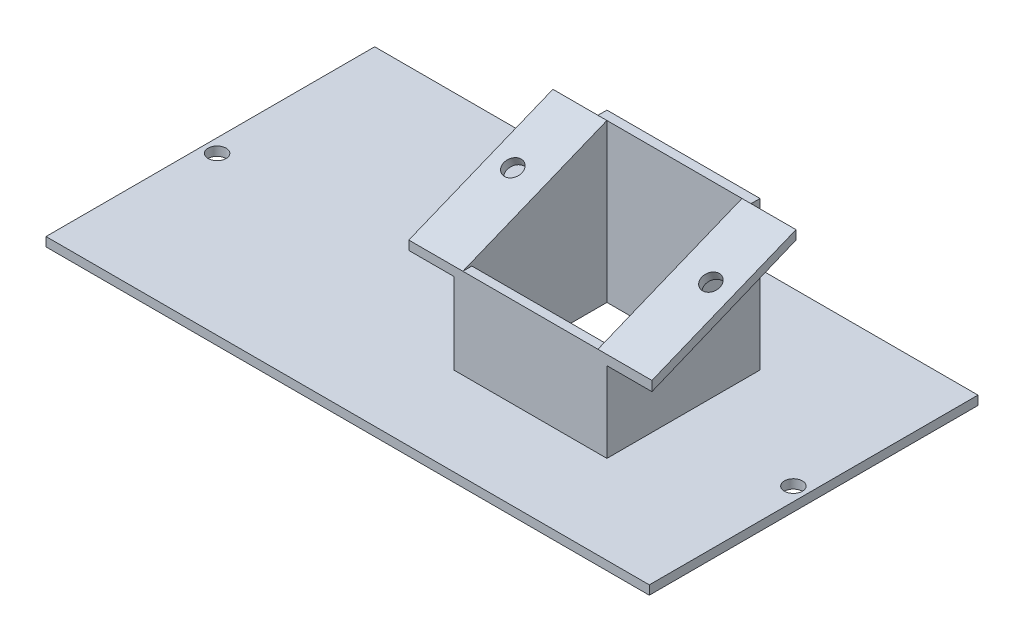
SolidWorks part; units mm, degrees
ref_plane "前视基准面" through (0, 0, 0) normal (0, 0, 1) x (1, 0, 0)
ref_plane "上视基准面" through (0, 0, 0) normal (0, 1, 0) x (1, 0, 0)
ref_plane "右视基准面" through (0, 0, 0) normal (1, 0, 0) x (0, 0, -1)
other "Configuration Table"
sketch "草图1" plane through (0, 0, 0) normal (0, 1, 0) x (1, 0, 0)
  line L1 (-76.1711, 41.9495) -> (57.8289, 41.9495)
  line L2 (-76.1711, 41.9495) -> (-76.1711, -31.0505)
  line L3 (-76.1711, -31.0505) -> (57.8289, -31.0505)
  line L4 (57.8289, 41.9495) -> (57.8289, -31.0505)
  line L9 (-3.2005, 20.5608) -> (26.7995, 20.5608)
  line L10 (-3.2005, 20.5608) -> (-3.2005, -9.4392)
  line L11 (-3.2005, -9.4392) -> (26.7995, -9.4392)
  line L12 (26.7995, 20.5608) -> (26.7995, -9.4392)
  circle A0 centre (-73.1711, 3.9495) radius 2
  circle A1 centre (54.8289, 3.9495) radius 2
  dimension "D5" = 35
  dimension "D6" = 3
  dimension "D7" = 35
  dimension "D8" = 3
  dimension "D1" = 73
  dimension "D2" = 134
  dimension "D3" = 30
  dimension "D4" = 30
extrude "凸台-拉伸1" add sketch "草图1" along normal blind 2
sketch "草图2" plane through (0, 2, 0) normal (0, 1, 0) x (1, 0, 0)
  line L1 (-3.2005, 20.5608) -> (26.7995, 20.5608)
  line L3 (-3.2005, 20.5608) -> (-3.2005, -9.4392)
  line L4 (-5.2005, 22.5608) -> (28.7995, 22.5608)
  line L5 (-5.2005, 22.5608) -> (-5.2005, -11.4392)
  line L6 (-5.2005, -11.4392) -> (28.7995, -11.4392)
  line L7 (28.7995, 22.5608) -> (28.7995, -11.4392)
  line L8 (-3.2005, -9.4392) -> (26.7995, -9.4392)
  line L9 (-5.2005, -11.4392) -> (-3.2005, -9.4392) construction
  line L10 (26.7995, 20.5608) -> (26.7995, -9.4392)
  point P9 (11.7995, 5.5608)
  dimension "D1" = 34
  dimension "D2" = 34
  dimension "D3" = 30
extrude "凸台-拉伸2" add sketch "草图2" along normal blind 20
sketch "草图3" plane through (0, 22, 0) normal (0, 1, 0) x (1, 0, 0)
  line L7 (-5.2005, 22.5608) -> (28.7995, 22.5608)
  line L8 (-5.2005, 22.5608) -> (-5.2005, 20.5608)
  line L9 (-5.2005, 20.5608) -> (28.7995, 20.5608)
  line L10 (28.7995, 22.5608) -> (28.7995, 20.5608)
  dimension "D1" = 2
  dimension "D2" = 34
extrude "凸台-拉伸4" add sketch "草图3" along normal blind 13
sketch "草图5" plane through (28.7995, 0, 0) normal (1, 0, 0) x (0, 0, -1)
  line L0 (-11.4392, 22) -> (20.5608, 22)
  line L1 (20.5608, 22) -> (20.5608, 35)
  line L2 (20.5608, 35) -> (-11.4392, 22)
extrude "凸台-拉伸5" add sketch "草图5" against normal blind 2
sketch "草图6" plane through (-5.2005, 0, 0) normal (-1, 0, 0) x (0, 0, 1)
  line L0 (-20.5608, 35) -> (-20.5608, 22)
  line L1 (-20.5608, 35) -> (-20.5608, 0) construction
  line L2 (-20.5608, 35) -> (-20.5608, 22) construction
  line L3 (-20.5608, 22) -> (11.4392, 22)
  line L4 (11.4392, 22) -> (-20.5608, 35)
extrude "凸台-拉伸6" add sketch "草图6" against normal blind 2
sketch "草图7" plane through (28.7995, 0, 0) normal (1, 0, 0) x (0, 0, -1)
  line L0 (-11.4392, 22) -> (20.5608, 35)
  line L2 (20.5608, 32.9979) -> (-11.4392, 19.8364)
  line L3 (-11.4392, 22) -> (-11.4392, 2) construction
  line L4 (-11.4392, 19.8364) -> (-11.4392, 22)
  line L5 (20.5608, 35) -> (20.5608, 32.9979)
  point P4 (0, 0)
sketch "草图8" plane through (-5.2005, 0, 0) normal (-1, 0, 0) x (0, 0, 1)
  line L0 (11.4392, 22) -> (11.4392, 2) construction
  line L1 (11.4392, 22) -> (11.4392, 20.0016)
  line L2 (11.4392, 20.0016) -> (-20.5608, 32.9893)
  line L4 (-20.5608, 35) -> (11.4392, 22)
  line L5 (-20.5608, 35) -> (-20.5608, 32.9893)
extrude "凸台-拉伸8" add sketch "草图8" along normal blind 10
extrude "凸台-拉伸9" add sketch "草图7" along normal blind 10
sketch "草图9" plane through (0, 22.8723, 9.2919) normal (0, 0.9265, 0.3764) x (1, 0, 0)
  line L0 (-15.2005, -2.3177) -> (-15.2005, 32.2221) construction
  line L1 (-15.2005, 32.2221) -> (-5.2005, 32.2221) construction
  line L2 (38.7995, 32.2221) -> (38.7995, -2.3177) construction
  line L3 (38.7995, 32.2221) -> (28.7995, 32.2221) construction
  line L4 (26.7995, 32.2221) -> (26.7995, -2.3177) construction
  circle A0 centre (-10.2005, 17.2221) radius 2
  circle A1 centre (33.7995, 17.2221) radius 2
  point P14 (0, 0)
  dimension "D1" = 5
  dimension "D2" = 15
  dimension "D3" = 5
  dimension "D4" = 15
extrude "切除-拉伸1" cut sketch "草图9" against normal blind 2
